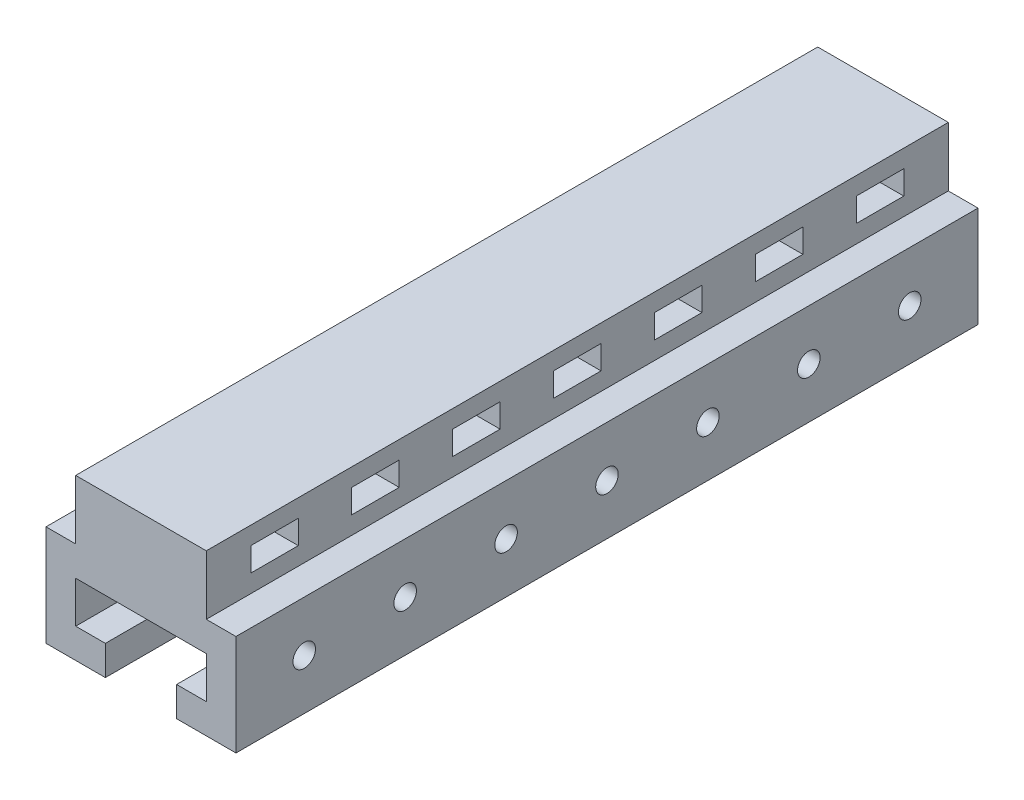
SolidWorks part; units mm, degrees
ref_plane "Спереди" through (0, 0, 0) normal (0, 0, 1) x (1, 0, 0)
ref_plane "Сверху" through (0, 0, 0) normal (0, 1, 0) x (1, 0, 0)
ref_plane "Справа" through (0, 0, 0) normal (1, 0, 0) x (0, 0, -1)
other "Configuration Table"
sketch "Sketch1" plane through (0, 0, 0) normal (0, 0, 1) x (1, 0, 0)
  line L0 (0, 13.4642) -> (0, -26.3494) construction
  line L1 (37.1088, -5) -> (11, -5) construction
  line L3 (11, 5) -> (-11, 5)
  line L4 (11, 5) -> (11, -5)
  line L6 (-11, 5) -> (-11, -5)
  line L7 (11, 5) -> (-11, -5) construction
  line L8 (11, -5) -> (-11, 5) construction
  line L10 (-16, -22) -> (-16, -5)
  line L11 (-16, -5) -> (-11, -5)
  line L12 (16, -22) -> (16, -5)
  line L14 (-11, -17) -> (-6, -17)
  line L15 (-11, -10) -> (11, -10)
  line L16 (-11, -10) -> (-11, -17)
  line L23 (11, -5) -> (16, -5)
  line L24 (-11, -5) -> (-33.4853, -5) construction
  line L25 (-6, -17) -> (-6, -22)
  line L26 (6, -17) -> (6, -22)
  line L27 (11, -17) -> (6, -17)
  line L28 (11, -10) -> (11, -17)
  line L29 (-6, -22) -> (-16, -22)
  line L30 (6, -22) -> (16, -22)
  line L31 (-16, -13.5) -> (16, -13.5) construction
  point P3 (0, 0)
  point P6 (0, 0)
  point P16 (0, -5)
  dimension "D1" = 22
  dimension "D2" = 32
  dimension "D3" = 10
  dimension "D4" = 5
  dimension "D5" = 5
  dimension "D6" = 7
  dimension "D7" = 10
extrude "Boss-Extrude1" add sketch "Sketch1" against normal blind 125
sketch "Sketch2" plane through (16, 0, 0) normal (1, 0, 0) x (0, 0, -1)
  line L0 (0, -13.5) -> (125, -13.5) construction
  line L1 (0, -10) -> (0, -17) construction
  line L2 (125, -22) -> (125, -5) construction
  line L3 (62.5, -13.5) -> (79.5, -13.5) construction
  line L4 (62.5, -13.5) -> (45.5, -13.5) construction
  circle A0 centre (62.5, -13.5) radius 1.9
  circle A1 centre (79.5, -13.5) radius 1.9
  circle A2 centre (96.5, -13.5) radius 1.9
  circle A3 centre (45.5, -13.5) radius 1.9
  circle A4 centre (28.5, -13.5) radius 1.9
  circle A5 centre (113.5, -13.5) radius 1.9
  circle A6 centre (11.5, -13.5) radius 1.9
  dimension "D1" = 3.8
  dimension "D3" = 17
  dimension "D5" = 17
  dimension "D2" = 4
  dimension "D4" = 4
extrude "Cut-Extrude1" cut sketch "Sketch2" along direction (-1, 0, 0) on the side against the normal through all
sketch "Sketch3" plane through (11, 0, 0) normal (1, 0, 0) x (0, 0, -1)
  line L0 (0, 0) -> (125, 0) construction
  line L1 (0, 5) -> (0, -5) construction
  line L2 (125, -5) -> (125, 5) construction
  line L3 (83.5, -2) -> (75.5, -2)
  line L4 (66.5, 2) -> (58.5, 2)
  line L5 (66.5, 2) -> (66.5, -2)
  line L6 (66.5, -2) -> (58.5, -2)
  line L7 (58.5, 2) -> (58.5, -2)
  line L8 (66.5, 2) -> (58.5, -2) construction
  line L9 (66.5, -2) -> (58.5, 2) construction
  line L10 (83.5, 2) -> (83.5, -2)
  line L11 (83.5, 2) -> (75.5, 2)
  line L12 (75.5, 2) -> (75.5, -2)
  line L13 (100.5, -2) -> (92.5, -2)
  line L14 (100.5, 2) -> (100.5, -2)
  line L15 (100.5, 2) -> (92.5, 2)
  line L16 (92.5, 2) -> (92.5, -2)
  line L17 (66.5, -2) -> (83.5, -2) construction
  line L18 (49.5, -2) -> (41.5, -2)
  line L19 (49.5, 2) -> (49.5, -2)
  line L20 (49.5, 2) -> (41.5, 2)
  line L21 (41.5, 2) -> (41.5, -2)
  line L22 (32.5, -2) -> (24.5, -2)
  line L23 (32.5, 2) -> (32.5, -2)
  line L24 (32.5, 2) -> (24.5, 2)
  line L25 (24.5, 2) -> (24.5, -2)
  line L26 (66.5, -2) -> (49.5, -2) construction
  line L27 (117.5, -2) -> (109.5, -2)
  line L28 (117.5, 2) -> (117.5, -2)
  line L29 (117.5, 2) -> (109.5, 2)
  line L30 (109.5, 2) -> (109.5, -2)
  line L31 (15.5, -2) -> (7.5, -2)
  line L32 (15.5, 2) -> (15.5, -2)
  line L33 (15.5, 2) -> (7.5, 2)
  line L34 (7.5, 2) -> (7.5, -2)
  point P6 (62.5, 0)
  dimension "D1" = 8
  dimension "D2" = 4
  dimension "D4" = 17
  dimension "D6" = 17
  dimension "D3" = 4
  dimension "D5" = 4
extrude "Cut-Extrude2" cut sketch "Sketch3" against normal through all
